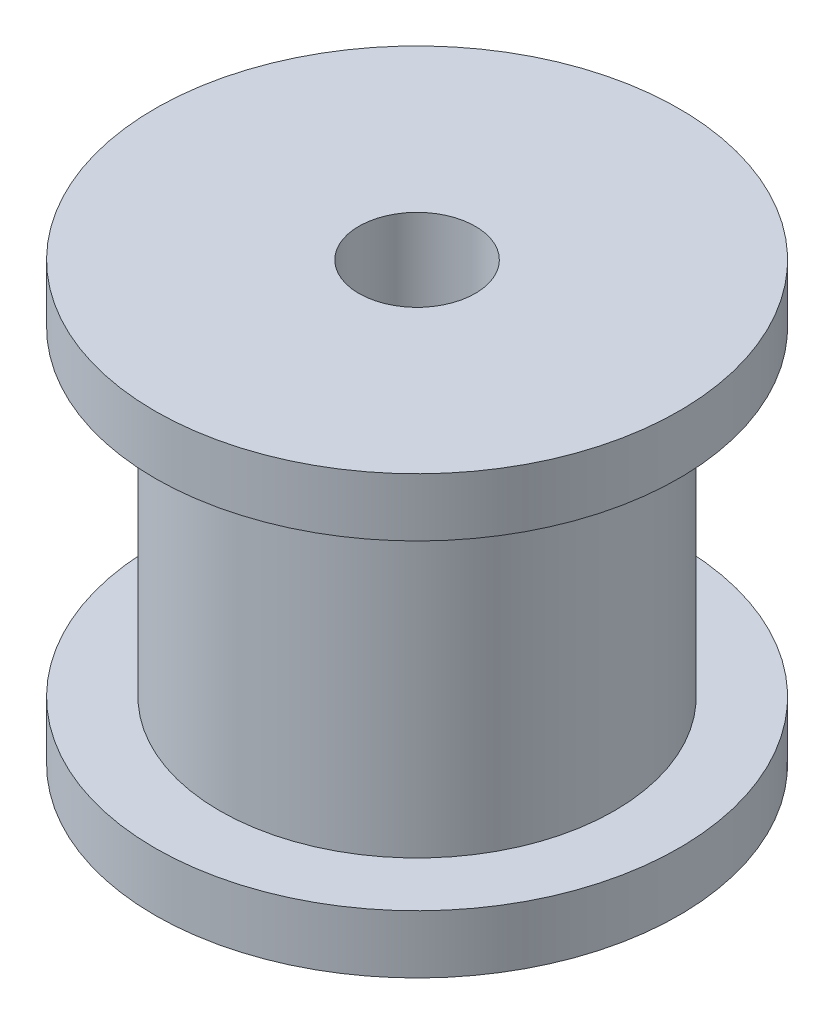
SolidWorks part; units mm, degrees
material "AISI 304"
ref_plane "前视基准面" through (0, 0, 0) normal (0, 0, 1) x (1, 0, 0)
ref_plane "上视基准面" through (0, 0, 0) normal (0, 1, 0) x (1, 0, 0)
ref_plane "右视基准面" through (0, 0, 0) normal (1, 0, 0) x (0, 0, -1)
other "Configuration Table"
sketch "草图1" plane through (0, 0, 0) normal (0, 1, 0) x (1, 0, 0)
  circle A0 centre (0, 0) radius 9
  dimension "D1" = 18
extrude "凸台-拉伸1" add sketch "草图1" along normal blind 2
sketch "草图2" plane through (0, 2, 0) normal (0, 1, 0) x (1, 0, 0)
  circle A0 centre (0, 0) radius 6.78
  dimension "D1" = 13.56
extrude "凸台-拉伸2" add sketch "草图2" along normal blind 11
sketch "草图3" plane through (0, 13, 0) normal (0, 1, 0) x (1, 0, 0)
  circle A0 centre (0, 0) radius 9
  dimension "D1" = 18
extrude "凸台-拉伸3" add sketch "草图3" along normal blind 2
sketch "草图4" plane through (0, 15, 0) normal (0, 1, 0) x (1, 0, 0)
  circle A0 centre (0, 0) radius 2
  dimension "D1" = 4
extrude "切除-拉伸1" cut sketch "草图4" against normal blind 26
